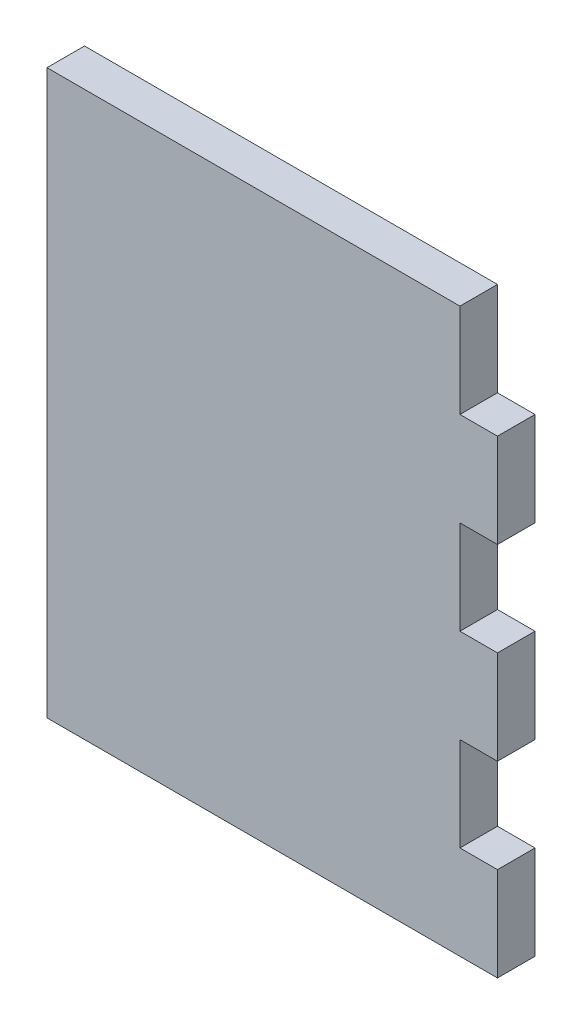
SolidWorks part; units mm, degrees
ref_plane "Спереди" through (0, 0, 0) normal (0, 0, 1) x (1, 0, 0)
ref_plane "Сверху" through (0, 0, 0) normal (0, 1, 0) x (1, 0, 0)
ref_plane "Справа" through (0, 0, 0) normal (1, 0, 0) x (0, 0, -1)
sketch "Эскиз2" plane through (0, 0, 0) normal (0, 0, 1) x (1, 0, 0)
  line L0 (0, 0) -> (60, 0)
  line L1 (60, 0) -> (60, 12.5)
  line L2 (60, 12.5) -> (55, 12.5)
  line L3 (55, 12.5) -> (55, 25)
  line L4 (55, 25) -> (60, 25)
  line L5 (60, 25) -> (60, 37.5)
  line L6 (60, 37.5) -> (55, 37.5)
  line L7 (55, 37.5) -> (55, 50)
  line L8 (55, 50) -> (60, 50)
  line L9 (60, 50) -> (60, 62.5)
  line L10 (60, 62.5) -> (55, 62.5)
  line L11 (55, 62.5) -> (55, 75)
  line L12 (55, 75) -> (0, 75)
  line L13 (0, 75) -> (0, 0)
  dimension "D1" = 60
  dimension "D2" = 75
  dimension "D3" = 5
extrude "Бобышка-Вытянуть1" add sketch "Эскиз2" along normal blind 5
